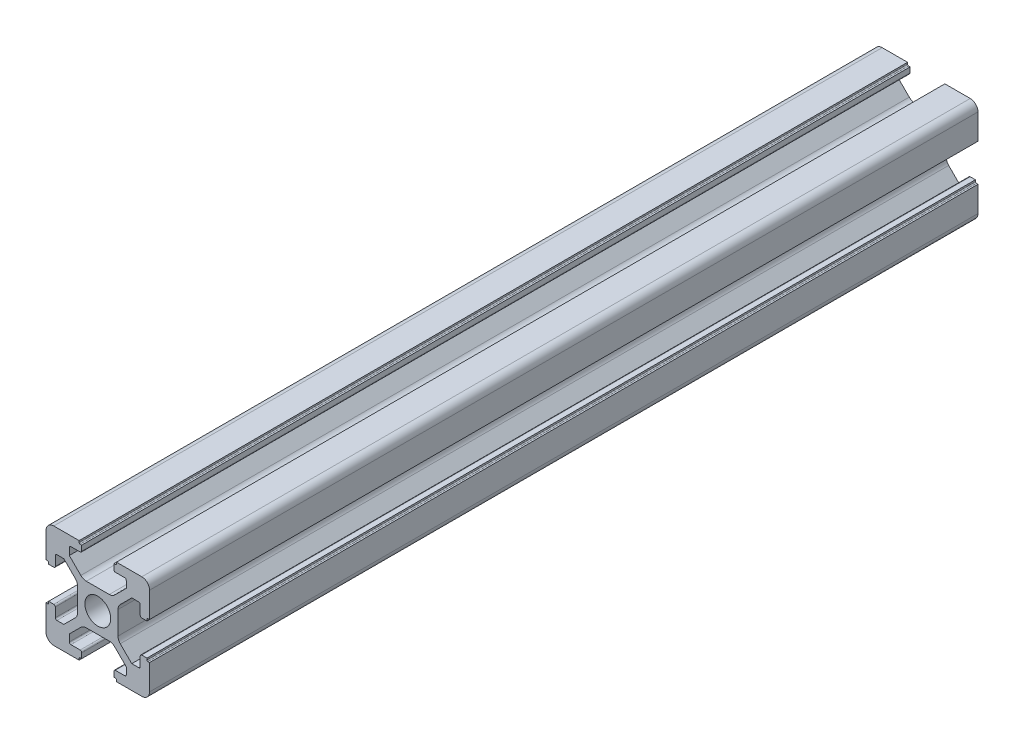
SolidWorks part; units mm, degrees
ref_plane "前视基准面" through (0, 0, 0) normal (0, 0, 1) x (1, 0, 0)
ref_plane "上视基准面" through (0, 0, 0) normal (0, 1, 0) x (1, 0, 0)
ref_plane "右视基准面" through (0, 0, 0) normal (1, 0, 0) x (0, 0, -1)
sketch "草图1" plane through (0, 0, 0) normal (0, 0, 1) x (1, 0, 0)
  line L0 (4.216, 3.2442) -> (6.4367, 5.4649)
  line L1 (6.4367, 5.4649) -> (7.7767, 5.4649)
  line L2 (8.0767, 5.1649) -> (8.0767, 3.3649)
  line L3 (8.3767, 3.0649) -> (9.3767, 3.0649)
  line L4 (9.3767, 3.0649) -> (9.3767, 3.3649)
  line L5 (9.5767, 3.5649) -> (9.8767, 3.5649)
  line L6 (9.8767, 3.5649) -> (9.8767, 8.4649)
  line L7 (8.3767, 9.9649) -> (3.4767, 9.9649)
  line L8 (3.4767, 9.9649) -> (3.4767, 9.6649)
  line L9 (3.2767, 9.4649) -> (2.9767, 9.4649)
  line L10 (2.9767, 9.4649) -> (2.9767, 8.4649)
  line L11 (3.2767, 8.1649) -> (5.0767, 8.1649)
  line L12 (5.3767, 7.8649) -> (5.3767, 6.5249)
  line L13 (5.3767, 6.5249) -> (3.156, 4.3042)
  line L14 (2.0953, 3.8649) -> (-2.342, 3.8649)
  line L15 (-3.4027, 4.3042) -> (-5.6233, 6.5249)
  line L16 (-5.6233, 6.5249) -> (-5.6233, 7.8649)
  line L17 (-5.3233, 8.1649) -> (-3.5233, 8.1649)
  line L18 (-3.2233, 8.4649) -> (-3.2233, 9.4649)
  line L19 (-3.2233, 9.4649) -> (-3.5233, 9.4649)
  line L20 (-3.7233, 9.6649) -> (-3.7233, 9.9649)
  line L21 (-3.7233, 9.9649) -> (-8.6233, 9.9649)
  line L22 (-10.1233, 8.4649) -> (-10.1233, 3.5649)
  line L23 (-10.1233, 3.5649) -> (-9.8233, 3.5649)
  line L24 (-9.6233, 3.3649) -> (-9.6233, 3.0649)
  line L25 (-9.6233, 3.0649) -> (-8.6233, 3.0649)
  line L26 (-8.3233, 3.3649) -> (-8.3233, 5.1649)
  line L27 (-8.0233, 5.4649) -> (-6.6833, 5.4649)
  line L28 (-6.6833, 5.4649) -> (-4.4627, 3.2442)
  line L29 (-4.0233, 2.1836) -> (-4.0233, -2.2538)
  line L30 (-4.4627, -3.3144) -> (-6.6833, -5.5351)
  line L31 (-6.6833, -5.5351) -> (-8.0233, -5.5351)
  line L32 (-8.3233, -5.2351) -> (-8.3233, -3.4351)
  line L33 (-8.6233, -3.1351) -> (-9.6233, -3.1351)
  line L34 (-9.6233, -3.1351) -> (-9.6233, -3.4351)
  line L35 (-9.8233, -3.6351) -> (-10.1233, -3.6351)
  line L36 (-10.1233, -3.6351) -> (-10.1233, -8.5351)
  line L37 (-8.6233, -10.0351) -> (-3.7233, -10.0351)
  line L38 (-3.7233, -10.0351) -> (-3.7233, -9.7351)
  line L39 (-3.5233, -9.5351) -> (-3.2233, -9.5351)
  line L40 (-3.2233, -9.5351) -> (-3.2233, -8.5351)
  line L41 (-3.5233, -8.2351) -> (-5.3233, -8.2351)
  line L42 (-5.6233, -7.9351) -> (-5.6233, -6.5951)
  line L43 (-5.6233, -6.5951) -> (-3.4027, -4.3744)
  line L44 (-2.342, -3.9351) -> (2.0953, -3.9351)
  line L45 (3.156, -4.3744) -> (5.3767, -6.5951)
  line L46 (5.3767, -6.5951) -> (5.3767, -7.9351)
  line L47 (5.0767, -8.2351) -> (3.2767, -8.2351)
  line L48 (2.9767, -8.5351) -> (2.9767, -9.5351)
  line L49 (2.9767, -9.5351) -> (3.2767, -9.5351)
  line L50 (3.4767, -9.7351) -> (3.4767, -10.0351)
  line L51 (3.4767, -10.0351) -> (8.3767, -10.0351)
  line L52 (9.8767, -8.5351) -> (9.8767, -3.6351)
  line L53 (9.8767, -3.6351) -> (9.5767, -3.6351)
  line L54 (9.3767, -3.4351) -> (9.3767, -3.1351)
  line L55 (9.3767, -3.1351) -> (8.3767, -3.1351)
  line L56 (8.0767, -3.4351) -> (8.0767, -5.2351)
  line L57 (7.7767, -5.5351) -> (6.4367, -5.5351)
  line L58 (6.4367, -5.5351) -> (4.216, -3.3144)
  line L59 (3.7767, -2.2538) -> (3.7767, 2.1836)
  circle A0 centre (-0.1233, -0.0351) radius 2.5
  arc A1 (8.0767, 5.1649) -> (7.7767, 5.4649) centre (7.7767, 5.1649) ccw
  arc A2 (8.0767, 3.3649) -> (8.3767, 3.0649) centre (8.3767, 3.3649) ccw
  arc A3 (9.5767, 3.5649) -> (9.3767, 3.3649) centre (9.5767, 3.3649) ccw
  arc A4 (9.8767, 8.4649) -> (8.3767, 9.9649) centre (8.3767, 8.4649) ccw
  arc A5 (3.2767, 9.4649) -> (3.4767, 9.6649) centre (3.2767, 9.6649) ccw
  arc A6 (2.9767, 8.4649) -> (3.2767, 8.1649) centre (3.2767, 8.4649) ccw
  arc A7 (5.3767, 7.8649) -> (5.0767, 8.1649) centre (5.0767, 7.8649) ccw
  arc A8 (2.0953, 3.8649) -> (3.156, 4.3042) centre (2.0953, 5.3649) ccw
  arc A9 (-3.4027, 4.3042) -> (-2.342, 3.8649) centre (-2.342, 5.3649) ccw
  arc A10 (-5.3233, 8.1649) -> (-5.6233, 7.8649) centre (-5.3233, 7.8649) ccw
  arc A11 (-3.5233, 8.1649) -> (-3.2233, 8.4649) centre (-3.5233, 8.4649) ccw
  arc A12 (-3.7233, 9.6649) -> (-3.5233, 9.4649) centre (-3.5233, 9.6649) ccw
  arc A13 (-8.6233, 9.9649) -> (-10.1233, 8.4649) centre (-8.6233, 8.4649) ccw
  arc A14 (-9.6233, 3.3649) -> (-9.8233, 3.5649) centre (-9.8233, 3.3649) ccw
  arc A15 (-8.6233, 3.0649) -> (-8.3233, 3.3649) centre (-8.6233, 3.3649) ccw
  arc A16 (-8.0233, 5.4649) -> (-8.3233, 5.1649) centre (-8.0233, 5.1649) ccw
  arc A17 (-4.0233, 2.1836) -> (-4.4627, 3.2442) centre (-5.5233, 2.1836) ccw
  arc A18 (-4.4627, -3.3144) -> (-4.0233, -2.2538) centre (-5.5233, -2.2538) ccw
  arc A19 (-8.3233, -5.2351) -> (-8.0233, -5.5351) centre (-8.0233, -5.2351) ccw
  arc A20 (-8.3233, -3.4351) -> (-8.6233, -3.1351) centre (-8.6233, -3.4351) ccw
  arc A21 (-9.8233, -3.6351) -> (-9.6233, -3.4351) centre (-9.8233, -3.4351) ccw
  arc A22 (-10.1233, -8.5351) -> (-8.6233, -10.0351) centre (-8.6233, -8.5351) ccw
  arc A23 (-3.5233, -9.5351) -> (-3.7233, -9.7351) centre (-3.5233, -9.7351) ccw
  arc A24 (-3.2233, -8.5351) -> (-3.5233, -8.2351) centre (-3.5233, -8.5351) ccw
  arc A25 (-5.6233, -7.9351) -> (-5.3233, -8.2351) centre (-5.3233, -7.9351) ccw
  arc A26 (-2.342, -3.9351) -> (-3.4027, -4.3744) centre (-2.342, -5.4351) ccw
  arc A27 (3.156, -4.3744) -> (2.0953, -3.9351) centre (2.0953, -5.4351) ccw
  arc A28 (5.0767, -8.2351) -> (5.3767, -7.9351) centre (5.0767, -7.9351) ccw
  arc A29 (3.2767, -8.2351) -> (2.9767, -8.5351) centre (3.2767, -8.5351) ccw
  arc A30 (3.4767, -9.7351) -> (3.2767, -9.5351) centre (3.2767, -9.7351) ccw
  arc A31 (8.3767, -10.0351) -> (9.8767, -8.5351) centre (8.3767, -8.5351) ccw
  arc A32 (9.3767, -3.4351) -> (9.5767, -3.6351) centre (9.5767, -3.4351) ccw
  arc A33 (8.3767, -3.1351) -> (8.0767, -3.4351) centre (8.3767, -3.4351) ccw
  arc A34 (7.7767, -5.5351) -> (8.0767, -5.2351) centre (7.7767, -5.2351) ccw
  arc A35 (3.7767, -2.2538) -> (4.216, -3.3144) centre (5.2767, -2.2538) ccw
  arc A36 (4.216, 3.2442) -> (3.7767, 2.1836) centre (5.2767, 2.1836) ccw
extrude "凸台-拉伸1" add sketch "草图1" along normal blind 160
